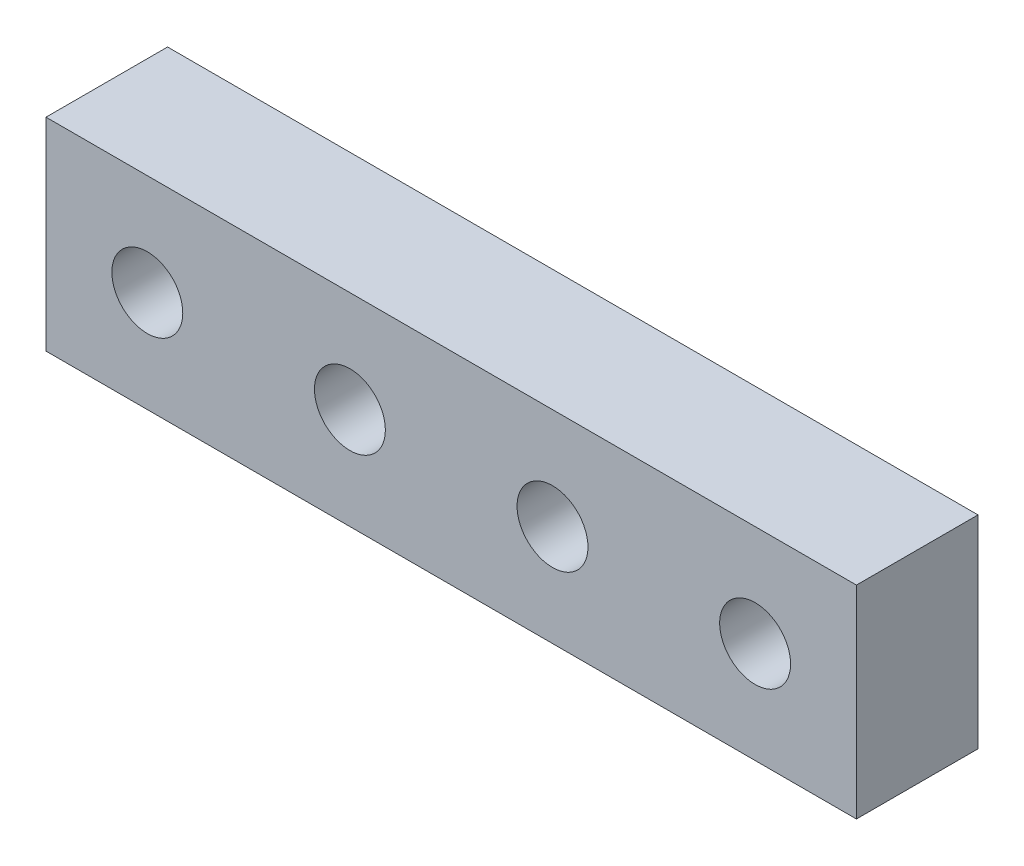
SolidWorks part; units mm, degrees
ref_plane "Plan de face" through (0, 0, 0) normal (0, 0, 1) x (1, 0, 0)
ref_plane "Plan de dessus" through (0, 0, 0) normal (0, 1, 0) x (1, 0, 0)
ref_plane "Plan de droite" through (0, 0, 0) normal (1, 0, 0) x (0, 0, -1)
sketch "Esquisse1" plane through (0, 0, 0) normal (0, 0, 1) x (1, 0, 0)
  line L0 (0, 5) -> (40, 5) construction
  line L1 (0, 0) -> (40, 0)
  line L2 (0, 0) -> (0, 10)
  line L3 (0, 10) -> (40, 10)
  line L4 (40, 0) -> (40, 10)
  circle A0 centre (5, 5) radius 1.75
  circle A1 centre (15, 5) radius 1.75
  circle A2 centre (25, 5) radius 1.75
  circle A3 centre (35, 5) radius 1.75
  dimension "D3" = 3.5
  dimension "D1" = 40
  dimension "D2" = 10
  dimension "D4" = 5
  dimension "D5" = 4
extrude "Boss.-Extru.1" add sketch "Esquisse1" along normal blind 6
